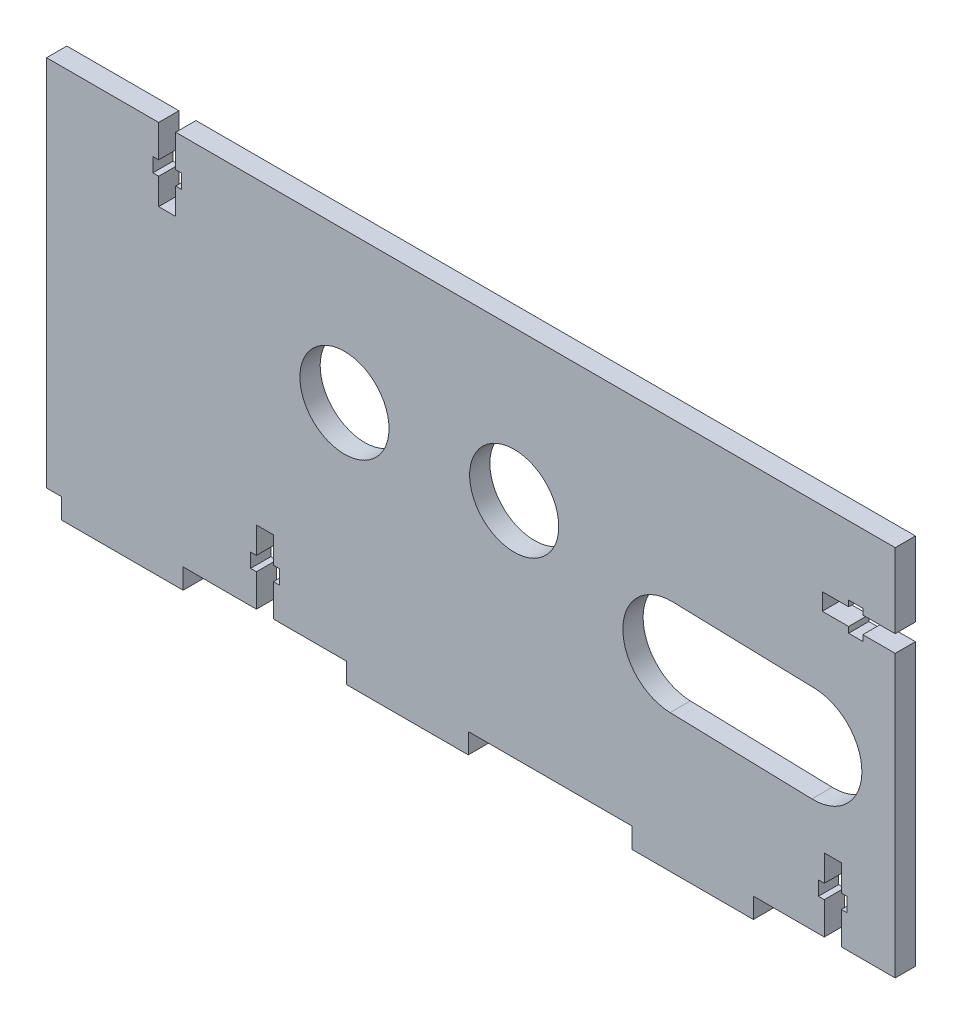
SolidWorks part; units mm, degrees
ref_plane "Front Plane" through (0, 0, 0) normal (0, 0, 1) x (1, 0, 0)
ref_plane "Top Plane" through (0, 0, 0) normal (0, 1, 0) x (1, 0, 0)
ref_plane "Right Plane" through (0, 0, 0) normal (1, 0, 0) x (0, 0, -1)
sketch "Sketch1" plane through (0, 0, 0) normal (0, 0, 1) x (1, 0, 0)
  line L1 (-115, -45) -> (115, -45)
  line L2 (-115, -45) -> (-115, 45)
  line L3 (-115, 45) -> (115, 45)
  line L4 (115, -45) -> (115, 45)
  line L5 (-115, -45) -> (115, 45) construction
  line L6 (-115, 45) -> (115, -45) construction
  point P0 (0, 0)
  dimension "D1" = 230
  dimension "D2" = 90
extrude "Boss-Extrude1" add sketch "Sketch1" along normal blind 5
sketch "Sketch2" plane through (0, 0, 5) normal (0, 0, 1) x (1, 0, 0)
  line L0 (-115, 10) -> (115, 10) construction
  line L1 (-115, 45) -> (-115, -45) construction
  line L2 (115, -45) -> (115, 45) construction
  circle A0 centre (-20.95, 10) radius 11
  circle A1 centre (20.95, 10) radius 11
  dimension "D2" = 22
  dimension "D1" = 41.9
  dimension "D3" = 20.95
  dimension "D7" = 10
extrude "Cut-Extrude1" cut sketch "Sketch2" against normal up to next
other "Move Face2" face at (0, 45, 2.5) parameters "D1"=2
sketch "Sketch3" plane through (0, 0, 5) normal (0, 0, 1) x (1, 0, 0)
  line L0 (-115, 47) -> (-115, -45) construction
  line L1 (-115, 41) -> (-106.4901, 41)
  line L2 (-115, 41) -> (-115, 47)
  line L3 (-115, 47) -> (-106.4901, 47)
  line L4 (-106.4901, 41) -> (-106.4901, 47)
  line L5 (115, 47) -> (-115, 47) construction
  line L6 (-106.4901, 41) -> (-106.4901, 47) construction
  line L7 (-119.2574, 41) -> (-106.4901, 41) construction
extrude "Cut-Extrude2" cut sketch "Sketch3" against normal blind 10
sketch "Sketch4" plane through (0, 0, 5) normal (0, 0, 1) x (1, 0, 0)
  line L0 (-125.7824, -45) -> (-125.7824, -39) construction
  line L1 (-125.7824, -39) -> (-137.7824, -39) construction
  line L2 (-135.9139, 10.6104) -> (-138.383, 1.3956)
  line L3 (-138.5403, -22.3736) -> (-141.6461, -33.9647) construction
  line L4 (-138.5403, -22.3736) -> (-144.3359, -20.8207) construction
  line L5 (-131.2552, 27.9971) -> (-125.4596, 26.4442) construction
  line L6 (-119.2574, 41) -> (-106.4901, 41) construction
  line L7 (-122.3538, 38.0353) -> (-125.4596, 26.4442) construction
  line L8 (-122.3538, 38.0353) -> (-122.1552, 38.7765) construction
  line L9 (-125.7824, -45) -> (-125.7824, -39)
  line L10 (-125.7824, -39) -> (-137.7824, -39)
  line L11 (-131.2552, 27.9971) -> (-133.3257, 20.2697)
  line L12 (-138.5403, -22.3736) -> (-141.6461, -33.9647)
  line L13 (-138.5403, -22.3736) -> (-144.3359, -20.8207)
  line L14 (-131.2552, 27.9971) -> (-125.4596, 26.4442)
  line L15 (-119.2574, 41) -> (-115, 41)
  line L16 (-122.3538, 38.0353) -> (-125.4596, 26.4442)
  line L17 (-122.3538, 38.0353) -> (-122.1552, 38.7765)
  line L18 (-125.7824, -45) -> (-115, -45)
  line L19 (-115, -45) -> (-115, 41)
  line L25 (-138.383, 1.3956) -> (-142.2467, 2.4309)
  line L26 (-142.2653, -13.0933) -> (-146.129, -12.058)
  line L27 (-142.2467, 2.4309) -> (-146.129, -12.058)
  line L28 (-132.0131, 40.6235) -> (-151.3054, -31.3765) construction
  line L29 (-142.2653, -13.0933) -> (-144.3359, -20.8207)
  line L30 (-133.3257, 20.2697) -> (-135.9139, 10.6104)
  arc A1 (-119.2574, 41) -> (-122.1552, 38.7765) centre (-119.2574, 38) ccw construction
  arc A2 (-141.6461, -33.9647) -> (-137.7824, -39) centre (-137.7824, -35) ccw construction
  arc A3 (-119.2574, 41) -> (-122.1552, 38.7765) centre (-119.2574, 38) ccw
  arc A4 (-141.6461, -33.9647) -> (-137.7824, -39) centre (-137.7824, -35) ccw
  dimension "D1" = 15
  dimension "D2" = 4
  dimension "D3" = 8
sketch "Sketch5" plane through (-129.462, 34.6892, 0) normal (0.9659, -0.2588, 0) x (0, 0, -1)
extrude "Boss-Extrude2" add sketch "Sketch4" against normal blind 5
sketch "Sketch6" plane through (0, 0, 5) normal (0, 0, 1) x (1, 0, 0)
  line L0 (-125.7824, -45) -> (115, -45) construction
  line L1 (-90.7824, -45) -> (-60.7824, -45)
  line L2 (-90.7824, -45) -> (-90.7824, -50)
  line L3 (-90.7824, -50) -> (-60.7824, -50)
  line L4 (-60.7824, -45) -> (-60.7824, -50)
  line L5 (-137.7824, -50) -> (120, -50) construction
  line L6 (-20.3912, -45) -> (9.6088, -45)
  line L15 (-20.3912, -45) -> (-20.3912, -50)
  line L16 (-20.3912, -50) -> (9.6088, -50)
  line L17 (9.6088, -45) -> (9.6088, -50)
  line L18 (50, -45) -> (80, -45)
  line L19 (50, -45) -> (50, -50)
  line L20 (50, -50) -> (80, -50)
  line L21 (80, -45) -> (80, -50)
  line L22 (-125.7824, -39) -> (-125.7824, -45) construction
  line L23 (115, -45) -> (115, 47) construction
  dimension "D1" = 30
  dimension "D2" = 3
  dimension "D3" = 35
  dimension "D4" = 35
extrude "Boss-Extrude3" add sketch "Sketch6" against normal blind 5
sketch "Sketch12" plane through (0, 0, 5) normal (0, 0, 1) x (1, 0, 0)
  line L0 (115, 47) -> (-106.4901, 47) construction
  line L1 (-94.4901, 47) -> (-168.7865, 47)
  line L2 (-94.4901, 47) -> (-94.4901, -57.3564)
  line L3 (-94.4901, -57.3564) -> (-168.7865, -57.3564)
  line L4 (-168.7865, 47) -> (-168.7865, -57.3564)
  line L5 (-106.4901, 41) -> (-106.4901, 47) construction
  dimension "D1" = 12
extrude "Cut-Extrude6" cut sketch "Sketch12" against normal blind 10
sketch "Sketch13" plane through (0, 0, 5) normal (0, 0, 1) x (1, 0, 0)
  line L120 (-38.4868, -37) -> (-37.0368, -37) construction
  line L121 (-38.4868, -45) -> (-38.4868, -37) construction
  line L122 (101.7, -37) -> (103.15, -37) construction
  line L123 (101.7, -45) -> (101.7, -37) construction
  line L124 (107, 28.603) -> (107, 30.053) construction
  line L125 (115, 28.603) -> (107, 28.603) construction
  line L126 (-66.8095, 39) -> (-68.2595, 39) construction
  line L127 (-66.8095, 47) -> (-66.8095, 39) construction
  line L128 (-37.0368, -37) -> (-37.0368, -33.5) construction
  line L129 (103.15, -37) -> (103.15, -33.5) construction
  line L130 (107, 30.053) -> (103.5, 30.053) construction
  line L131 (-68.2595, 39) -> (-68.2595, 35.5) construction
  line L132 (-37.0368, -33.5) -> (-38.4868, -33.5) construction
  line L133 (103.15, -33.5) -> (101.7, -33.5) construction
  line L134 (103.5, 30.053) -> (103.5, 28.603) construction
  line L135 (-68.2595, 35.5) -> (-66.8095, 35.5) construction
  line L136 (-38.4868, -33.5) -> (-38.4868, -27) construction
  line L137 (101.7, -33.5) -> (101.7, -27) construction
  line L138 (103.5, 28.603) -> (97, 28.603) construction
  line L139 (-66.8095, 35.5) -> (-66.8095, 29) construction
  line L140 (-38.4868, -45) -> (-42.6868, -45) construction
  line L141 (101.7, -45) -> (97.5, -45) construction
  line L142 (115, 28.603) -> (115, 24.403) construction
  line L143 (-66.8095, 47) -> (-62.6095, 47) construction
  line L144 (-42.6868, -27) -> (-38.4868, -27) construction
  line L145 (97.5, -27) -> (101.7, -27) construction
  line L146 (97, 24.403) -> (97, 28.603) construction
  line L147 (-62.6095, 29) -> (-66.8095, 29) construction
  line L148 (-42.6868, -33.5) -> (-42.6868, -27) construction
  line L149 (97.5, -33.5) -> (97.5, -27) construction
  line L150 (103.5, 24.403) -> (97, 24.403) construction
  line L151 (-62.6095, 35.5) -> (-62.6095, 29) construction
  line L152 (-44.1368, -33.5) -> (-42.6868, -33.5) construction
  line L153 (96.05, -33.5) -> (97.5, -33.5) construction
  line L154 (103.5, 22.953) -> (103.5, 24.403) construction
  line L155 (-61.1595, 35.5) -> (-62.6095, 35.5) construction
  line L156 (-44.1368, -37) -> (-44.1368, -33.5) construction
  line L157 (96.05, -37) -> (96.05, -33.5) construction
  line L158 (107, 22.953) -> (103.5, 22.953) construction
  line L159 (-61.1595, 39) -> (-61.1595, 35.5) construction
  line L160 (-42.6868, -37) -> (-44.1368, -37) construction
  line L161 (97.5, -37) -> (96.05, -37) construction
  line L162 (107, 24.403) -> (107, 22.953) construction
  line L163 (-62.6095, 39) -> (-61.1595, 39) construction
  line L164 (-42.6868, -45) -> (-42.6868, -37) construction
  line L165 (97.5, -45) -> (97.5, -37) construction
  line L166 (115, 24.403) -> (107, 24.403) construction
  line L167 (-62.6095, 47) -> (-62.6095, 39) construction
  line L168 (-38.4868, -37) -> (-37.0368, -37)
  line L169 (-38.4868, -45) -> (-38.4868, -37)
  line L170 (101.7, -37) -> (103.15, -37)
  line L171 (101.7, -45) -> (101.7, -37)
  line L172 (107, 28.603) -> (107, 30.053)
  line L173 (115, 28.603) -> (107, 28.603)
  line L174 (-66.8095, 39) -> (-68.2595, 39)
  line L175 (-66.8095, 47) -> (-66.8095, 39)
  line L176 (-37.0368, -37) -> (-37.0368, -33.5)
  line L177 (103.15, -37) -> (103.15, -33.5)
  line L178 (107, 30.053) -> (103.5, 30.053)
  line L179 (-68.2595, 39) -> (-68.2595, 35.5)
  line L180 (-37.0368, -33.5) -> (-38.4868, -33.5)
  line L181 (103.15, -33.5) -> (101.7, -33.5)
  line L182 (103.5, 30.053) -> (103.5, 28.603)
  line L183 (-68.2595, 35.5) -> (-66.8095, 35.5)
  line L184 (-38.4868, -33.5) -> (-38.4868, -27)
  line L185 (101.7, -33.5) -> (101.7, -27)
  line L186 (103.5, 28.603) -> (97, 28.603)
  line L187 (-66.8095, 35.5) -> (-66.8095, 29)
  line L188 (-38.4868, -45) -> (-42.6868, -45)
  line L189 (101.7, -45) -> (97.5, -45)
  line L190 (115, 28.603) -> (115, 24.403)
  line L191 (-66.8095, 47) -> (-62.6095, 47)
  line L192 (-42.6868, -27) -> (-38.4868, -27)
  line L193 (97.5, -27) -> (101.7, -27)
  line L194 (97, 24.403) -> (97, 28.603)
  line L195 (-62.6095, 29) -> (-66.8095, 29)
  line L196 (-42.6868, -33.5) -> (-42.6868, -27)
  line L197 (97.5, -33.5) -> (97.5, -27)
  line L198 (103.5, 24.403) -> (97, 24.403)
  line L199 (-62.6095, 35.5) -> (-62.6095, 29)
  line L200 (-44.1368, -33.5) -> (-42.6868, -33.5)
  line L201 (96.05, -33.5) -> (97.5, -33.5)
  line L202 (103.5, 22.953) -> (103.5, 24.403)
  line L203 (-61.1595, 35.5) -> (-62.6095, 35.5)
  line L204 (-44.1368, -37) -> (-44.1368, -33.5)
  line L205 (96.05, -37) -> (96.05, -33.5)
  line L206 (107, 22.953) -> (103.5, 22.953)
  line L207 (-61.1595, 39) -> (-61.1595, 35.5)
  line L208 (-42.6868, -37) -> (-44.1368, -37)
  line L209 (97.5, -37) -> (96.05, -37)
  line L210 (107, 24.403) -> (107, 22.953)
  line L211 (-62.6095, 39) -> (-61.1595, 39)
  line L212 (-42.6868, -45) -> (-42.6868, -37)
  line L213 (97.5, -45) -> (97.5, -37)
  line L214 (115, 24.403) -> (107, 24.403)
  line L215 (-62.6095, 47) -> (-62.6095, 39)
extrude "Cut-Extrude7" cut sketch "Sketch13" against normal blind 10
sketch "Sketch14" plane through (0, 0, 5) normal (0, 0, 1) x (1, 0, 0)
  line L0 (94.7732, -5) -> (59.7732, -4.0484) construction
  line L1 (94.447, -16.9956) -> (59.447, -16.0439)
  line L2 (95.0993, 6.9956) -> (60.0993, 7.9472)
  arc A0 (94.447, -16.9956) -> (95.0993, 6.9956) centre (94.7732, -5) ccw
  circle A2 centre (94.7732, -5) radius 15 construction
  arc A3 (60.0993, 7.9472) -> (59.447, -16.0439) centre (59.7732, -4.0484) ccw
  point P1 (77.2732, -4.5242)
  dimension "D2" = 12
extrude "Cut-Extrude8" cut sketch "Sketch14" against normal blind 10
